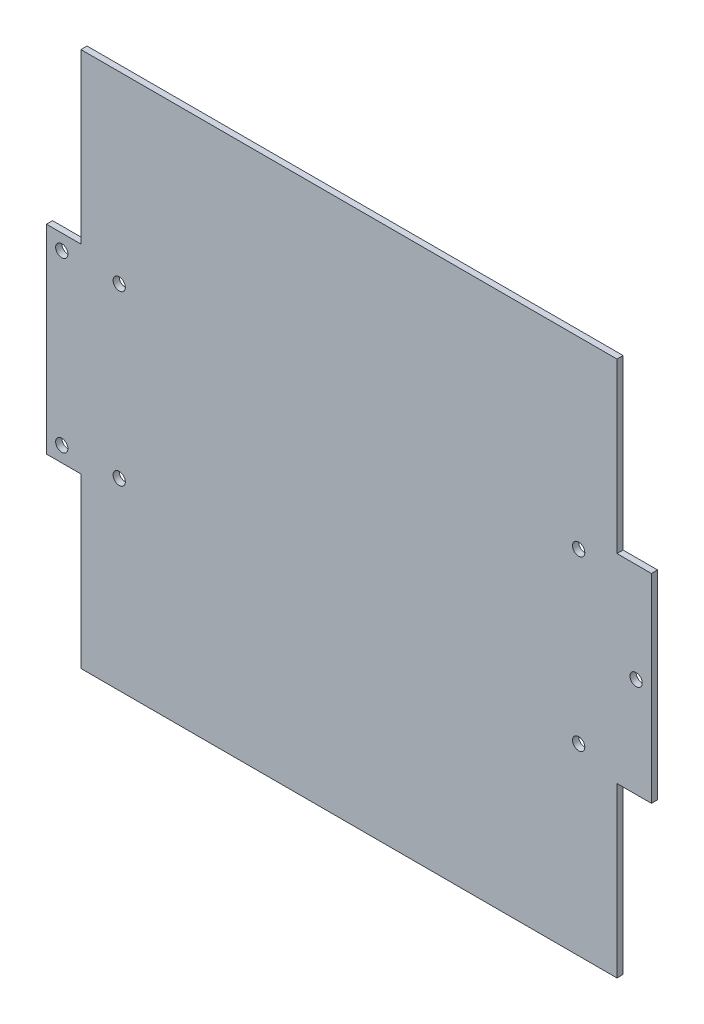
SolidWorks part; units mm, degrees
material "Custom Plastic"
ref_plane "Front Plane" through (0, 0, 0) normal (0, 0, 1) x (1, 0, 0)
ref_plane "Top Plane" through (0, 0, 0) normal (0, 1, 0) x (1, 0, 0)
ref_plane "Right Plane" through (0, 0, 0) normal (1, 0, 0) x (0, 0, -1)
sketch "Sketch1" plane through (0, 0, 0) normal (0, 0, 1) x (1, 0, 0)
  line L0 (138, 70) -> (-2, 70) construction
  line L1 (0, 0) -> (140, 0)
  line L2 (0, 0) -> (0, 44)
  line L3 (0, 140) -> (140, 140)
  line L4 (140, 0) -> (140, 44)
  line L5 (0, 96) -> (-9, 96)
  line L6 (-9, 96) -> (-9, 44)
  line L7 (-9, 44) -> (0, 44)
  line L8 (140, 44) -> (149, 44)
  line L9 (149, 44) -> (149, 96)
  line L10 (149, 96) -> (140, 96)
  line L11 (-2, 70) -> (-9, 70) construction
  line L12 (0, 96) -> (0, 140)
  line L13 (140, 96) -> (140, 140)
  dimension "D2" = 9
  dimension "D3" = 52
  dimension "D1" = 140
  dimension "D5" = 140
extrude "Boss-Extrude1" add sketch "Sketch1" along normal blind 1.6
hole_wizard "Ø3.2 (3.2) Diameter Hole1" positions "Sketch6" profile "Sketch5" hole size "Ø3.2" standard "Ansi Metric"
sketch "Sketch6" plane through (0, 0, 0) normal (0, 0, -1) x (-1, 0, 0)
  line L0 (6.0733, 70) -> (-132.5, 70) construction
  line L5 (-130, 92) -> (-130, 48) construction
  line L9 (-70, 140) -> (-70, 0) construction
  line L10 (-140, 140) -> (0, 140) construction
  line L11 (0, 0) -> (-140, 0) construction
  line L13 (-10, 92) -> (-10, 48) construction
  line L14 (-146.0733, 70) -> (-7.5, 70) construction
  point P20 (-130, 92)
  point P22 (-130, 48)
  point P48 (-10, 92)
  point P50 (-10, 48)
  dimension "D1" = 60
  dimension "D3" = 22
  dimension "D4" = 44
sketch "Sketch5" plane through (130, 92, 0) normal (1, 0, 0) x (0, 1, 0)
  line L0 (0, 0) -> (0, 4.9614)
  line L1 (0, 4.9614) -> (1.6, 4)
  line L2 (1.6, 4) -> (1.6, 0)
  line L5 (1.6, 0) -> (0, 0)
  line L10 (0, 4.9614) -> (-1.6, 4) construction
  line L11 (0, -6.35) -> (0, 107.95) construction
  dimension "Hole Dia." = 3.2
  dimension "Hole Depth" = 4
  dimension "Drill Angle" = 118
sketch "Sketch7" plane through (0, 0, 0) normal (0, 0, -1) x (-1, 0, 0)
  line L0 (-70, 140) -> (-70, 0) construction
  line L1 (-140, 140) -> (0, 140) construction
  line L2 (0, 0) -> (-140, 0) construction
  line L3 (-61.8, 132) -> (-78.2, 132) construction
  circle A0 centre (-78.2, 132) radius 1.5
  circle A1 centre (-61.8, 132) radius 1.5
  dimension "D2" = 3
  dimension "D3" = 8.2
  dimension "D1" = 8.2
  dimension "D4" = 8
extrude "Cut-Extrude1" [suppressed] cut sketch "Sketch7" against normal through all
sketch "Sketch8" plane through (0, 0, 1.6) normal (0, 0, 1) x (1, 0, 0)
  line L1 (10, 92) -> (-5, 92) construction
  line L2 (10, 92) -> (10, 48) construction
  line L3 (10, 48) -> (-5, 48) construction
  line L4 (-5, 92) -> (-5, 48) construction
  line L5 (130, 92) -> (145, 92) construction
  line L6 (130, 92) -> (130, 48) construction
  line L7 (130, 48) -> (145, 48) construction
  line L8 (145, 92) -> (145, 48) construction
  circle A0 centre (-5, 92) radius 1.6
  circle A1 centre (-5, 48) radius 1.6
  circle A2 centre (145, 70) radius 1.6
  dimension "D2" = 3.2
  dimension "D1" = 15
extrude "Cut-Extrude2" cut sketch "Sketch8" against normal through all
